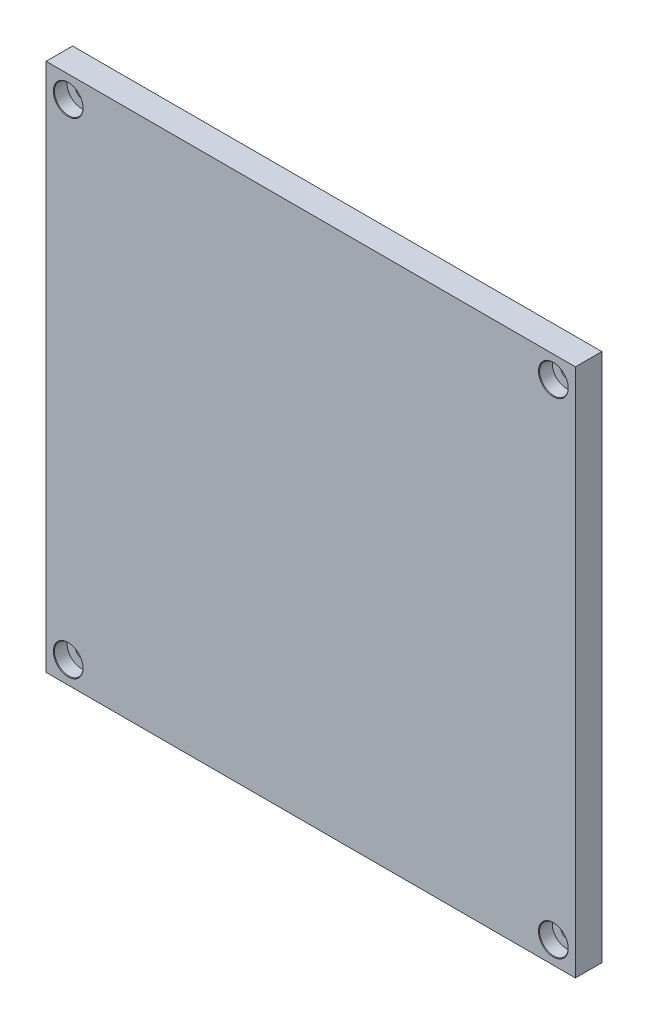
SolidWorks part; units mm, degrees
ref_plane "Front Plane" through (0, 0, 0) normal (1, 0, 0) x (0, 1, 0)
ref_plane "Top Plane" through (0, 0, 0) normal (0, 0, 1) x (0, 1, 0)
ref_plane "Right Plane" through (0, 0, 0) normal (0, 1, 0) x (-1, 0, 0)
sketch "Sketch1" plane through (0, 0, 0) normal (0, 0, 1) x (0, 1, 0)
  line L1 (-60, -60) -> (60, -60)
  line L2 (-60, -60) -> (-60, 60)
  line L3 (-60, 60) -> (60, 60)
  line L4 (60, -60) -> (60, 60)
  line L5 (-60, -60) -> (60, 60) construction
  line L6 (-60, 60) -> (60, -60) construction
  point P0 (0, 0)
  dimension "D1" = 120
  dimension "D2" = 120
extrude "Boss-Extrude1" add sketch "Sketch1" along normal blind 6
sketch "Sketch2" plane through (0, 0, 6) normal (0, 0, 1) x (1, 0, 0)
  line L0 (-60, 60) -> (-50, 60)
  line L1 (-60, 60) -> (-60, 50)
  line L2 (-60, 50) -> (-50, 50)
  line L3 (-50, 60) -> (-50, 50)
  line L4 (45, 60) -> (45, 45)
  line L5 (60, 45) -> (45, 45)
  line L6 (60, 60) -> (60, 45)
  line L7 (60, 60) -> (45, 60)
  line L8 (60, -60) -> (45, -60)
  line L9 (60, -60) -> (60, -45)
  line L10 (60, -45) -> (45, -45)
  line L11 (45, -60) -> (45, -45)
  line L12 (-45, -60) -> (-45, -45)
  line L13 (-60, -45) -> (-45, -45)
  line L14 (-60, -60) -> (-60, -45)
  line L15 (-60, -60) -> (-45, -60)
  circle A0 centre (-55, 55) radius 1.25
  point P28 (-55, 55)
  dimension "D2" = 2.5
  dimension "D4" = 5
  dimension "D1" = 10
  dimension "D3" = 10
  dimension "D5" = 5
hole_wizard "CBORE for M3 SBHCS1" positions "Sketch2" profile "Sketch7" counterbore size "M3" standard "ANSI Metric" end condition through all
sketch "Sketch7" plane through (-55, 55, 6) normal (1, 0, 0) x (0, -1, 0)
  line L0 (0, 0) -> (0, 6)
  line L1 (0, 6) -> (1.25, 6)
  line L3 (1.25, 6) -> (1.25, 3)
  line L4 (3.25, 3) -> (1.25, 3)
  line L5 (3.25, 3) -> (3.25, 0.125)
  line L6 (3.25, 0.125) -> (3.375, 0)
  line L7 (3.375, 0) -> (0, 0)
  line L8 (-3.25, 0.125) -> (-3.375, 0) construction
  line L11 (0, -6.35) -> (0, 107.95) construction
  dimension "Thru Hole Dia." = 2.5
  dimension "Thru Hole Depth" = 6
  dimension "C'Bore Dia." = 6.5
  dimension "C'Bore Depth" = 3
  dimension "Near C'Sink Dia." = 6.75
  dimension "Near C'Sink Angle" = 90
mirror "Mirror2" about plane through (0, 0, 0) normal (1, 0, 0) of "CBORE for M3 SBHCS1" second plane through (0, 0, 0) second plane normal (0, 1, 0)
sketch "Sketch9" plane through (0, 0, 6) normal (0, 0, 1) x (1, 0, 0)
  line L0 (3.3, 0) -> (-3.3, 0) construction
  line L1 (-27.75, -16.8) -> (27.75, -16.8)
  line L2 (-27.75, -16.8) -> (-27.75, 16.8)
  line L3 (-27.75, 16.8) -> (27.75, 16.8)
  line L4 (27.75, -16.8) -> (27.75, 16.8)
  line L5 (-27.75, -16.8) -> (27.75, 16.8) construction
  line L6 (-27.75, 16.8) -> (27.75, -16.8) construction
  circle A0 centre (-21.0438, 0) radius 1.15
  point P0 (0, 0)
  point P6 (-21.0438, 0)
  dimension "D3" = 2.3
  dimension "D1" = 55.5
  dimension "D2" = 33.6
